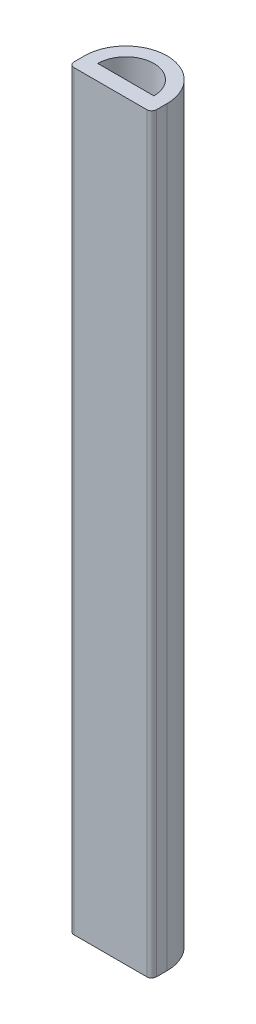
SolidWorks part; units mm, degrees
ref_plane "Front Plane" through (0, 0, 0) normal (0, 0, 1) x (1, 0, 0)
ref_plane "Top Plane" through (0, 0, 0) normal (0, 1, 0) x (1, 0, 0)
ref_plane "Right Plane" through (0, 0, 0) normal (1, 0, 0) x (0, 0, -1)
sketch "Sketch1" plane through (0, 0, 0) normal (0, 1, 0) x (1, 0, 0)
  line L0 (-6.35, 0) -> (6.35, 0)
  line L1 (-9.35, 0) -> (-9.35, -3.5)
  line L2 (-9.35, -3.5) -> (9.35, -3.5)
  line L3 (9.35, -3.5) -> (9.35, 0)
  arc A0 (6.35, 0) -> (-6.35, 0) centre (0, 0) ccw
  arc A1 (9.35, 0) -> (-9.35, 0) centre (0, 0) ccw
  dimension "D1" = 12.7
  dimension "D3" = 3.5
  dimension "D2" = 3
extrude "semicircular tube" add sketch "Sketch1" along normal blind 170
fillet "fillet edges" radius 1.1 2 edges at (-9.35, 85, 3.5) (9.35, 85, 3.5)
